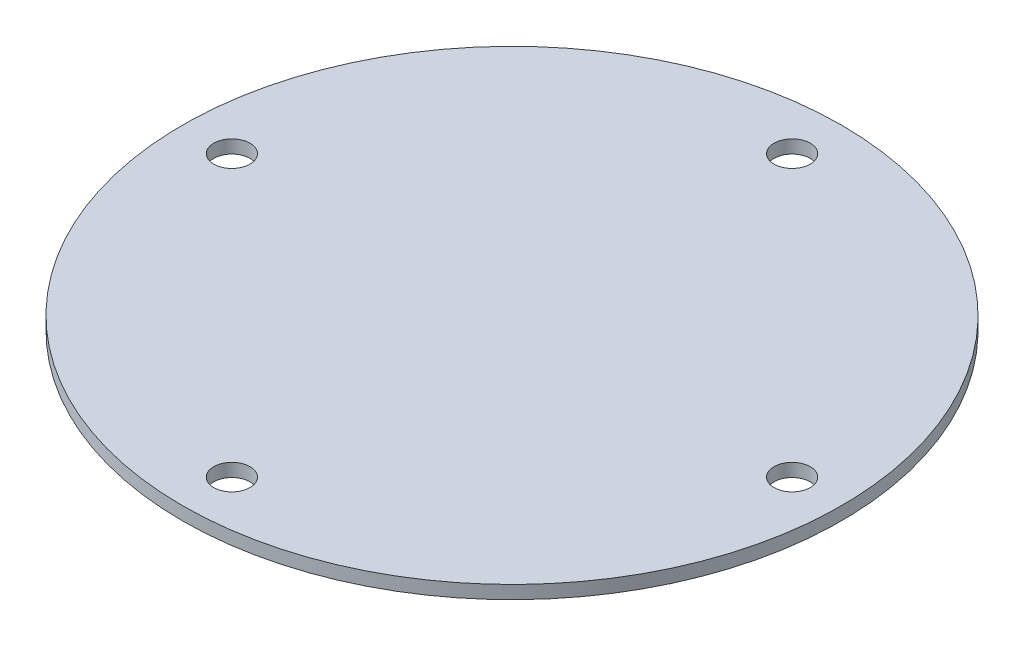
SolidWorks part; units mm, degrees
ref_plane "Front Plane" through (0, 0, 0) normal (0, 0, 1) x (1, 0, 0)
ref_plane "Top Plane" through (0, 0, 0) normal (0, 1, 0) x (1, 0, 0)
ref_plane "Right Plane" through (0, 0, 0) normal (1, 0, 0) x (0, 0, -1)
sketch "Sketch1" plane through (0, 0, 0) normal (0, 1, 0) x (1, 0, 0)
  circle A0 centre (0, 0) radius 50
  circle A2 centre (0, 0) radius 42.5 construction
  circle A3 centre (0, 42.5) radius 2.75
  circle A4 centre (42.5, 0) radius 2.75
  circle A5 centre (0, -42.5) radius 2.75
  circle A6 centre (-42.5, 0) radius 2.75
  point P15 (0, 0)
  dimension "D1" = 100
  dimension "D2" = 7.5
  dimension "D3" = 5.5
  dimension "D4" = 4
extrude "Boss-Extrude1" add sketch "Sketch1" along normal blind 2
